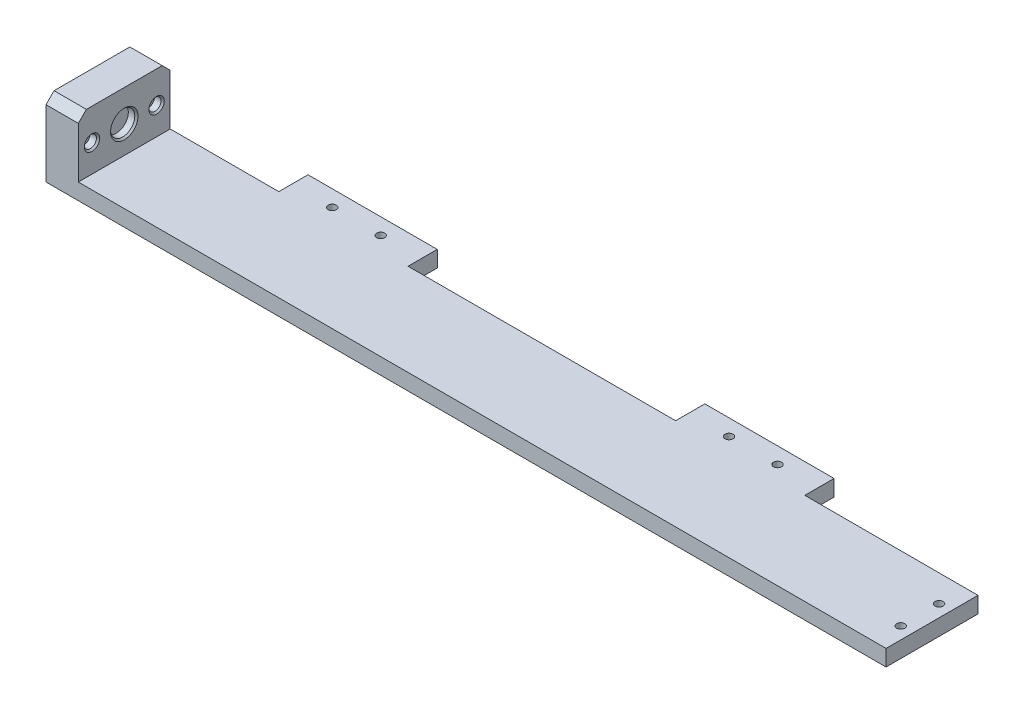
SolidWorks part; units mm, degrees
ref_plane "前视基准面" through (0, 0, 0) normal (0, 0, 1) x (1, 0, 0)
ref_plane "上视基准面" through (0, 0, 0) normal (0, 1, 0) x (1, 0, 0)
ref_plane "右视基准面" through (0, 0, 0) normal (1, 0, 0) x (0, 0, -1)
other "Configuration Table"
sketch "草图1" plane through (0, 0, 0) normal (0, 1, 0) x (1, 0, 0)
  line L1 (-105.6081, 28.4715) -> (105.6081, 28.4715)
  line L2 (-105.6081, 28.4715) -> (-105.6081, -28.4715)
  line L3 (-105.6081, -28.4715) -> (105.6081, -28.4715)
  line L4 (105.6081, 28.4715) -> (105.6081, -28.4715)
  line L5 (-105.6081, 28.4715) -> (105.6081, -28.4715) construction
  line L6 (-105.6081, -28.4715) -> (105.6081, 28.4715) construction
  point P0 (0, 0)
extrude "凸台-拉伸1" add sketch "草图1" along normal blind 20
sketch "草图2" plane through (0, 20, 0) normal (0, 1, 0) x (1, 0, 0)
  line L0 (-165.625, -56.909) -> (-325.625, -56.909) construction
  line L1 (500, 56.909) -> (-500, 56.909)
  line L2 (500, 56.909) -> (500, -56.909)
  line L3 (500, -56.909) -> (-500, -56.909)
  line L4 (-500, 56.909) -> (-500, -56.909)
  line L5 (500, 56.909) -> (-500, -56.909) construction
  line L6 (500, -56.909) -> (-500, 56.909) construction
  point P0 (0, 0)
  dimension "D1" = 1000
extrude "凸台-拉伸2" add sketch "草图2" against normal blind 20
sketch "草图3" plane through (0, 20, 0) normal (0, 1, 0) x (1, 0, 0)
  line L0 (500, 56.909) -> (-500, 56.909) construction
  line L1 (-325.625, 93.091) -> (-165.625, 93.091)
  line L2 (-325.625, 93.091) -> (-325.625, 56.909)
  line L3 (-325.625, 56.909) -> (-165.625, 56.909)
  line L4 (-165.625, 93.091) -> (-165.625, 56.909)
  line L5 (-165.625, -56.909) -> (-165.625, 93.091) construction
extrude "凸台-拉伸3" add sketch "草图3" against normal blind 20
sketch "草图4" plane through (0, 20, 0) normal (0, 1, 0) x (1, 0, 0)
  line L0 (325.625, -56.909) -> (325.625, 93.091) construction
  line L1 (165.625, 93.091) -> (325.625, 93.091)
  line L2 (165.625, 93.091) -> (165.625, 56.909)
  line L3 (165.625, 56.909) -> (325.625, 56.909)
  line L4 (325.625, 93.091) -> (325.625, 56.909)
  line L5 (500, 56.909) -> (-165.625, 56.909) construction
  point P9 (0, 0)
extrude "凸台-拉伸4" add sketch "草图4" against normal blind 20
sketch "草图5" plane through (0, 0, 56.909) normal (0, 0, 1) x (1, 0, 0)
  line L1 (-500, 20) -> (-460, 20)
  line L2 (-500, 20) -> (-500, 92.9306)
  line L3 (-500, 92.9306) -> (-460, 92.9306)
  line L4 (-460, 20) -> (-460, 92.9306)
  dimension "D1" = 40
extrude "凸台-拉伸5" add sketch "草图5" against normal up to surface (113.8179 mm away) up to face at (-412.8125, 10, -56.909)
sketch "草图6" plane through (-460, 0, 0) normal (1, 0, 0) x (0, 0, -1)
  circle A0 centre (0, 53.8253) radius 15
  circle A1 centre (40, 53.8253) radius 7.5
  circle A3 centre (-40, 53.8253) radius 7.5
extrude "切除-拉伸1" cut sketch "草图6" against normal blind 10 and the other way through all
sketch "草图7" plane through (500, 0, 0) normal (1, 0, 0) x (0, 0, -1)
  line L1 (-56.909, 20) -> (56.909, 20)
  line L2 (-56.909, 20) -> (-56.909, 0)
  line L3 (-56.909, 0) -> (56.909, 0)
  line L4 (56.909, 20) -> (56.909, 0)
extrude "凸台-拉伸6" add sketch "草图7" along normal blind 40
sketch "草图8" plane through (0, 20, 0) normal (0, 1, 0) x (1, 0, 0)
  circle A0 centre (525, 23.75) radius 5
  circle A1 centre (525, -23.75) radius 5
extrude "切除-拉伸2" cut sketch "草图8" against normal through all both and the other way through all
chamfer "倒角1" distance 10 angle 45 2 edges at (-480, 92.9306, -56.909) (-480, 92.9306, 56.909)
chamfer "倒角2" distance 2 angle 45 3 edges at (-460, 53.8253, 32.5) (-460, 53.8253, -15) (-460, 53.8253, -47.5)
sketch "草图9" plane through (0, 20, 0) normal (0, 1, 0) x (1, 0, 0)
  line L0 (-325.625, 93.091) -> (-325.625, 73.091) construction
  line L1 (-325.625, 73.091) -> (-165.625, 73.091) construction
  line L2 (-165.625, 73.091) -> (-165.625, 93.091) construction
  line L3 (-165.625, 93.091) -> (-325.625, 93.091) construction
  line L4 (-165.625, 56.909) -> (-165.625, 93.091) construction
  line L5 (-165.625, 93.091) -> (-325.625, 93.091) construction
  line L6 (165.625, 73.091) -> (325.625, 73.091) construction
  line L7 (165.625, 93.091) -> (165.625, 56.909) construction
  line L8 (325.625, 56.909) -> (325.625, 93.091) construction
  circle A0 centre (-275.625, 73.091) radius 5
  circle A1 centre (-215.625, 73.091) radius 5
  circle A2 centre (215.625, 73.091) radius 5
  circle A3 centre (275.625, 73.091) radius 5
  dimension "D1" = 10
  dimension "D2" = 10
  dimension "D3" = 50
  dimension "D4" = 50
  dimension "D6" = 10
  dimension "D7" = 50
  dimension "D8" = 50
  dimension "D5" = 20
extrude "切除-拉伸3" cut sketch "草图9" against normal blind 300
